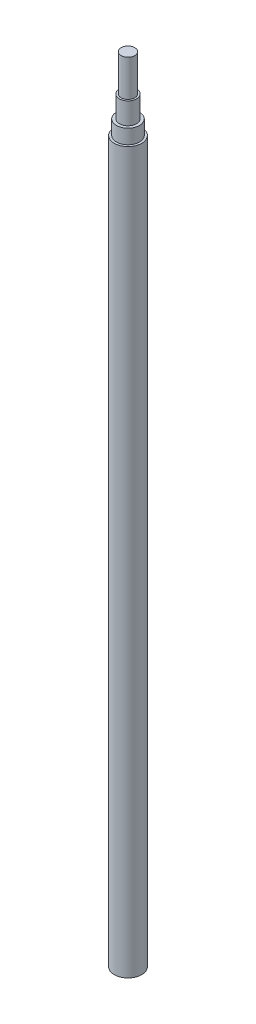
SolidWorks part; units mm, degrees
ref_plane "Front Plane" through (0, 0, 0) normal (0, 0, 1) x (1, 0, 0)
ref_plane "Top Plane" through (0, 0, 0) normal (0, 1, 0) x (1, 0, 0)
ref_plane "Right Plane" through (0, 0, 0) normal (1, 0, 0) x (0, 0, -1)
sketch "Sketch1" plane through (0, 0, 0) normal (0, 1, 0) x (1, 0, 0)
  circle A0 centre (0, 0) radius 9.525
  dimension "D1" = 19.05
extrude "Boss-Extrude1" add sketch "Sketch1" along normal blind 500
sketch "Sketch2" plane through (0, 500, 0) normal (0, 1, 0) x (1, 0, 0)
  circle A0 centre (0, 0) radius 8
  dimension "D1" = 16
extrude "Boss-Extrude2" add sketch "Sketch2" along normal blind 10
sketch "Sketch3" plane through (0, 510, 0) normal (0, 1, 0) x (1, 0, 0)
  circle A0 centre (0, 0) radius 6
  dimension "D1" = 12
extrude "Boss-Extrude3" add sketch "Sketch3" along normal blind 15
sketch "Sketch4" plane through (0, 525, 0) normal (0, 1, 0) x (1, 0, 0)
  circle A0 centre (0, 0) radius 4.7625
  dimension "D1" = 9.525
extrude "Boss-Extrude4" add sketch "Sketch4" along normal blind 25.4
ref_plane "Plane2" through (0, 435, 0) normal (0, 1, 0) x (1, 0, 0)
sketch "Sketch6" plane through (0, 435, 0) normal (0, 1, 0) x (1, 0, 0)
  line L0 (-14.9999, -20.3933) -> (-14.8628, -2.0244)
  line L1 (14.8631, -2.0218) -> (15, -20.3934)
  line L2 (-14.9999, -20.3933) -> (-27.4993, -37.387)
  line L3 (15, -20.3934) -> (27.4993, -37.387)
  line L4 (-27.4993, -37.387) -> (-27.4993, -78.3409)
  line L5 (-27.4993, -78.3409) -> (-7.4993, -78.3409)
  line L6 (-7.4993, -78.3409) -> (-7.4993, -68.3409)
  line L7 (-7.4993, -68.3409) -> (7.5007, -68.3409)
  line L8 (7.5007, -68.3409) -> (7.5007, -78.3409)
  line L9 (7.5007, -78.3409) -> (27.4993, -78.3409)
  line L10 (27.4993, -37.387) -> (27.4993, -78.3409)
  circle A0 centre (0, 0) radius 15
  circle A1 centre (-17.4993, -68.8682) radius 5
  circle A2 centre (17.4993, -68.8682) radius 5
  dimension "D1" = 30
  dimension "D7" = 10
  dimension "D8" = 10
  dimension "D2" = 10
  dimension "D3" = 54.9986
  dimension "D4" = 15
  dimension "D5" = 20
  dimension "D6" = 19.9986
  dimension "D9" = 10
  dimension "D10" = 10
